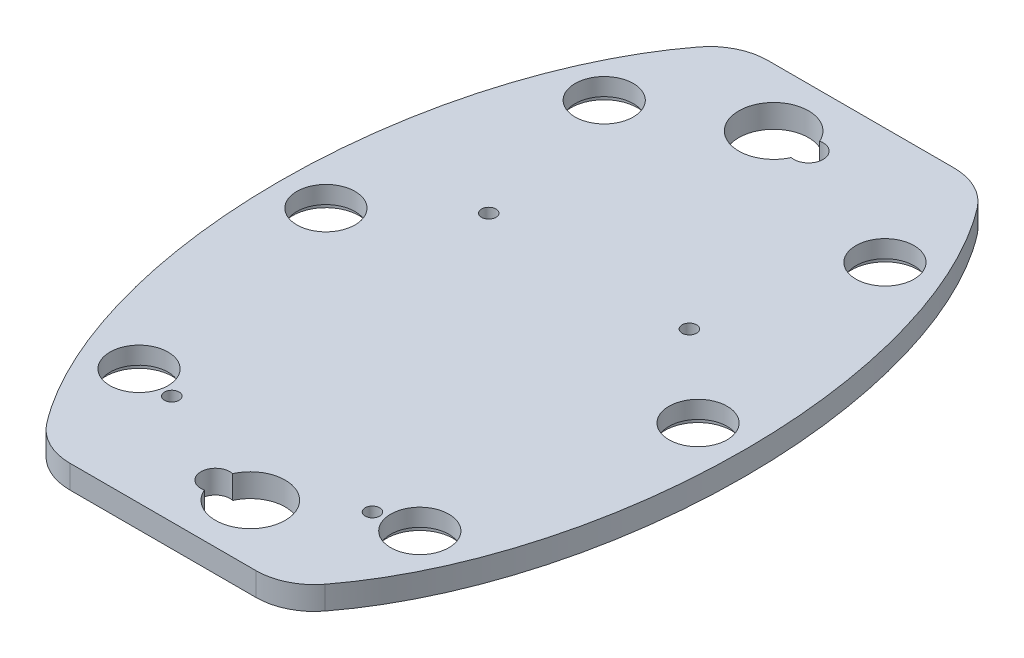
SolidWorks part; units mm, degrees
ref_plane "Front Plane" through (0, 0, 0) normal (0, 0, 1) x (1, 0, 0)
ref_plane "Top Plane" through (0, 0, 0) normal (0, 1, 0) x (1, 0, 0)
ref_plane "Right Plane" through (0, 0, 0) normal (1, 0, 0) x (0, 0, -1)
sketch "Sketch1" plane through (0, 0, 0) normal (0, 1, 0) x (1, 0, 0)
  line L0 (0, 122.4977) -> (0, -122.1819) construction
  line L1 (-179.9579, 0) -> (190.3765, 0) construction
  line L2 (-15.9996, 60) -> (15.9996, 60)
  line L3 (-15.9996, -60) -> (15.9996, -60)
  line L4 (-15.9996, -52) -> (15.9996, -52) construction
  line L5 (-15.9996, 52) -> (15.9996, 52) construction
  line L6 (-5, 50) -> (12.3874, 50) construction
  line L7 (3.5, 56.1073) -> (3.5, 43.072) construction
  line L8 (5, -50) -> (-12.3143, -50) construction
  arc A0 (-15.9996, -60) -> (-23.943, -56.0747) centre (-15.9996, -50) cw
  arc A1 (15.9996, -60) -> (23.943, -56.0747) centre (15.9996, -50) ccw
  arc A2 (15.9996, 60) -> (23.943, 56.0747) centre (15.9996, 50) cw
  arc A3 (-15.9996, 60) -> (-23.943, 56.0747) centre (-15.9996, 50) ccw
  arc A4 (-15.9996, -52) -> (-17.5882, -51.2149) centre (-15.9996, -50) cw construction
  arc A5 (15.9996, -52) -> (17.5882, -51.2149) centre (15.9996, -50) ccw construction
  arc A6 (15.9996, 52) -> (17.5882, 51.2149) centre (15.9996, 50) cw construction
  arc A7 (-15.9996, 52) -> (-17.5882, 51.2149) centre (-15.9996, 50) ccw construction
  circle A8 centre (-32, 0) radius 5
  circle A9 centre (-24.1415, 40) radius 5
  circle A10 centre (-24.1415, -40) radius 5
  circle A11 centre (24.1415, -40) radius 5
  circle A12 centre (32, 0) radius 5
  circle A13 centre (24.1415, 40) radius 5
  arc A15 (-0.4792, -52.4451) -> (-0.4792, -47.5549) centre (5, -50) ccw
  arc A16 (0.4792, 52.4451) -> (0.4792, 47.5549) centre (-5, 50) ccw
  arc A17 (0.4792, 47.5549) -> (0.4792, 52.4451) centre (1, 50) ccw
  arc A18 (-0.4792, -47.5549) -> (-0.4792, -52.4451) centre (-1, -50) ccw
  ellipse E0 centre (0, 0) end of major axis (0, 70) minor radius 40 (23.943, -56.0747) -> (23.943, 56.0747) ccw
  ellipse E1 centre (0, 0) end of major axis (0, 70) minor radius 40 (-25.4375, -54.0219) -> (0, -70) ccw construction
  ellipse E2 centre (0, 0) end of major axis (0, 70) minor radius 40 (0, -70) -> (25.4375, -54.0219) ccw construction
  ellipse E3 centre (0, 0) end of major axis (0, 70) minor radius 40 (-23.943, 56.0747) -> (-23.943, -56.0747) ccw
  ellipse E4 centre (0, 0) end of major axis (0, 70) minor radius 40 (25.4375, 54.0219) -> (0, 70) ccw construction
  ellipse E5 centre (0, 0) end of major axis (0, 70) minor radius 40 (0, 70) -> (-25.4375, 54.0219) ccw construction
  spline S0 degree 1 poles (-17.5882, 51.2149) (-17.5882, -51.2149) knots 0 0 1 1 construction
  spline S1 degree 1 poles (17.5882, -51.2149) (17.5882, 51.2149) knots 0 0 1 1 construction
  spline S2 degree 3 poles (-17.5882, 51.2149) (-17.8543, 50.867) (-18.3717, 50.1696) (-19.4032, 48.6946) (-20.6562, 46.7374) (-22.0999, 44.2045) (-23.1384, 42.1571) (-23.9184, 40.4997) (-24.7782, 38.5871) (-26.2892, 34.8562) (-28.1412, 29.2339) (-29.8405, 22.3295) (-31.2856, 13.872) (-32.021, 5.0754) (-32.021, -5.0754) (-31.2856, -13.872) (-29.8405, -22.3295) (-28.1412, -29.2339) (-26.2892, -34.8562) (-24.7782, -38.5871) (-23.9184, -40.4997) (-23.1384, -42.1571) (-22.0999, -44.2045) (-20.6562, -46.7374) (-19.4032, -48.6946) (-18.3717, -50.1696) (-17.8543, -50.867) (-17.5882, -51.2149) knots 0.641722 0.641722 0.641722 0.641722 0.670755 0.699789 0.757856 0.815923 0.87399 0.889719 0.918753 0.990125 1.106259 1.222393 1.338528 1.512729 1.628864 1.803065 1.919199 2.035334 2.151468 2.22284 2.251874 2.267602 2.32567 2.383737 2.441804 2.470838 2.499871 2.499871 2.499871 2.499871 construction
  spline S3 degree 3 poles (17.5882, -51.2149) (17.8543, -50.867) (18.3717, -50.1696) (19.4032, -48.6946) (20.6562, -46.7374) (22.0999, -44.2045) (23.9292, -40.5982) (26.0162, -35.685) (28.1412, -29.2339) (29.8405, -22.3295) (31.492, -12.6638) (32.3386, 0) (31.492, 12.6638) (29.8405, 22.3295) (28.1412, 29.2339) (26.0162, 35.685) (23.9292, 40.5982) (22.0999, 44.2045) (20.6562, 46.7374) (19.4032, 48.6946) (18.3717, 50.1696) (17.8543, 50.867) (17.5882, 51.2149) knots -2.499871 -2.499871 -2.499871 -2.499871 -2.470838 -2.441804 -2.383737 -2.32567 -2.267602 -2.151468 -2.035334 -1.919199 -1.803065 -1.570796 -1.338528 -1.222393 -1.106259 -0.990125 -0.87399 -0.815923 -0.757856 -0.699789 -0.670755 -0.641722 -0.641722 -0.641722 -0.641722 construction
  dimension "D4" = 10
  dimension "D7" = 10
  dimension "D10" = 12
  dimension "D13" = 5
  dimension "D17" = 5
  dimension "D1" = 60
  dimension "D2" = 40
  dimension "D3" = 70
  dimension "D5" = 60
  dimension "D8" = 40
  dimension "D9" = 40
  dimension "D11" = 50
  dimension "D12" = 5
  dimension "D14" = 6
  dimension "D15" = 50
  dimension "D16" = 5
  dimension "D18" = 6
  dimension "D6" = 8
extrude "Boss-Extrude1" add sketch "Sketch1" along normal blind 4
sketch "Sketch3" plane through (0, 0, 0) normal (0, -1, 0) x (1, 0, 0)
  circle A0 centre (-24.1415, -40) radius 5 construction
  circle A1 centre (-24.1415, -40) radius 5 construction
  circle A2 centre (-24.1415, -40) radius 5.75
  circle A3 centre (24.1415, 40) radius 5 construction
  circle A4 centre (-24.1415, 40) radius 5 construction
  circle A5 centre (-32, 0) radius 5 construction
  circle A6 centre (32, 0) radius 5 construction
  circle A7 centre (24.1415, -40) radius 5 construction
  circle A8 centre (24.1415, 40) radius 5 construction
  circle A9 centre (-24.1415, 40) radius 5 construction
  circle A10 centre (-32, 0) radius 5 construction
  circle A11 centre (32, 0) radius 5 construction
  circle A12 centre (24.1415, -40) radius 5 construction
  circle A13 centre (24.1415, -40) radius 5.75
  circle A14 centre (32, 0) radius 5.75
  circle A15 centre (24.1415, 40) radius 5.75
  circle A16 centre (-24.1415, 40) radius 5.75
  circle A17 centre (-32, 0) radius 5.75
  dimension "D1" = 11.5
extrude "Cut-Extrude2" cut sketch "Sketch3" against normal blind 1
sketch3d "3DSketch1"
  point P0 (40, 0, 60)
sketch3d "3DSketch2"
  point P0 (40, 0, 60)
sketch3d "3DSketch3"
  point P0 (40, 0, -60)
sketch "Sketch4" plane through (0, 4, 0) normal (0, 1, 0) x (1, 0, 0)
  line L3 (0, 83.9383) -> (0, -109.3849) construction
  line L7 (-15.9996, -60) -> (15.9996, -60) construction
  line L8 (-15.9996, -60) -> (15.9996, -60) construction
  line L9 (81.7532, -41.25) -> (-74.2904, -41.25) construction
  line L10 (102.7892, 13.25) -> (-68.0826, 13.25) construction
  line L11 (17.25, -41.25) -> (17.25, 13.25) construction
  line L12 (-17.25, -41.25) -> (-17.25, 13.25) construction
  circle A4 centre (17.25, -41.25) radius 1.25
  circle A5 centre (17.25, 13.25) radius 1.25
  circle A6 centre (-17.25, 13.25) radius 1.25
  circle A7 centre (-17.25, -41.25) radius 1.25
  dimension "D1" = 2.5
  dimension "D5" = 18.75
  dimension "D6" = 54.5
  dimension "D7" = 34.5
  dimension "D8" = 17.25
extrude "Cut-Extrude3" cut sketch "Sketch4" against normal up to next
